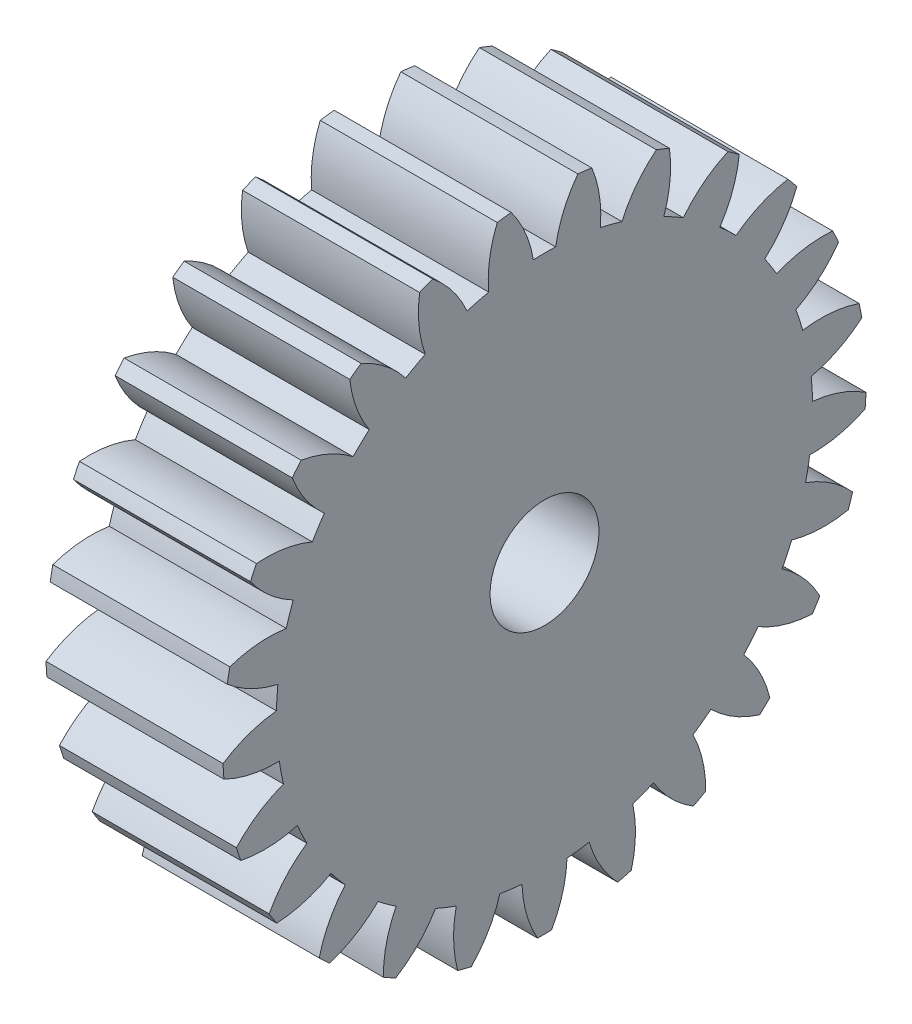
SolidWorks part; units mm, degrees
ref_plane "Plane1" through (0, 0, 0) normal (0, 0, 1) x (1, 0, 0)
ref_plane "Plane2" through (0, 0, 0) normal (0, 1, 0) x (1, 0, 0)
ref_plane "Plane3" through (0, 0, 0) normal (1, 0, 0) x (0, 0, -1)
sketch "HoldingSke" plane through (0, 0, 0) normal (0, 1, 0) x (1, 0, 0)
  line L0 (0, 0) -> (0.5179, -0.2415)
  line L1 (-15, 0) -> (100, 0) construction
  line L2 (0, 0) -> (-2.1039, 2.3779)
  line L3 (0, 0) -> (-11.863, 4.5341)
  line L4 (0, 0) -> (7.8269, 3.6497)
  line L5 (0, 0) -> (-46.8476, -17.4728)
  line L6 (0, 0) -> (-10.7765, -7.2709)
  line L7 (-2.1039, 2.3779) -> (8.6586, 51.2059)
  line L8 (-76.2, 54.61) -> (-74.8, 54.61)
  line L9 (-71.009, 38.7566) -> (-53.1078, 45.2721)
  line L10 (-76.2, 71.12) -> (104.1128, 71.12)
  line L11 (0, 0) -> (-13, 0)
  line L12 (-76.2, 101.6) -> (-76.147, 101.6)
  line L13 (24.9733, 27.94) -> (52.9518, 28.4284)
  line L14 (24.9733, 27.94) -> (24.9743, 27.94)
  line L15 (24.9733, 27.94) -> (100.4006, 29.5858)
  line L16 (-63.627, -1.75) -> (-12.827, -1.75)
  circle A0 centre (0, 0) radius 4
  circle A1 centre (0, 0) radius 19.6865
  circle A2 centre (0, 0) radius 37.5
  circle A3 centre (0, 0) radius 4
  dimension "MHD" = 39.373
  dimension "Hub_dia" = 75
  dimension "Bore" = 8
  dimension "MBD" = 8
  dimension "Num_teeth" = 25
  dimension "Pitch" = 0.5714
  dimension "Overall_len" = 50
  dimension "Show_teeth" = 25
  dimension "Thickness" = 13
  dimension "OAL" = 50.0001
  dimension "T_dim" = 1.4
  dimension "Ap" = 20
  dimension "H" = 19.05
  dimension "Pitch_radius" = 180.3128
  dimension "Width" = 13
  dimension "Backlash" = 0.053
  dimension "Addendum_fac" = 1
  dimension "Dedendum_fac" = 1.25
  dimension "Clearance_fac" = 0.25
  dimension "Dedendum_add" = 0.001
  dimension "Module" = 1.75
sketch "BasProSke" plane through (0, 0, 0) normal (0, 1, 0) x (1, 0, 0)
  line L0 (-10, 0) -> (60, 0) construction
  line L1 (0, 0) -> (0, 23.625)
  line L2 (0, 0) -> (13, 0)
  line L3 (13, 0) -> (13, 23.625)
  line L4 (13, 23.625) -> (0, 23.625)
  dimension "Thickness" = 13
  dimension "Diameter" = 47.25
revolve "Base-Revolve" add sketch "BasProSke" angle 360 about L0
sketch "TooCutSke" plane through (0, 0, 0) normal (1, 0, 0) x (0, 0, -1)
  line L1 (0, 0) -> (0, 107) construction
  line L2 (0, 0) -> (-1.4663, 21.8258) construction
  line L3 (0, 0) -> (-5.4739, 43.3306) construction
  line L4 (-1.4663, 21.8258) -> (-2.737, 21.6653) construction
  arc A0 (0.819, 19.6695) -> (-0.819, 19.6695) centre (0, 0) ccw
  arc A1 (2.4674, 23.5213) -> (-2.4674, 23.5213) centre (0, 0) ccw
  circle A2 centre (0, 0) radius 21.875 construction
  circle A3 centre (0, 0) radius 20.5558 construction
  arc A4 (-0.819, 19.6695) -> (-2.4674, 23.5213) centre (-9.4536, 18.2529) ccw
  arc A5 (2.4674, 23.5213) -> (0.819, 19.6695) centre (9.4536, 18.2529) ccw
  dimension "Root_dia" = 39.373
  dimension "Overcut_dia" = 47.3008
  dimension "Pitch_dia" = 43.75
  dimension "Base_dia" = 41.1116
  dimension "Flank_rad" = 8.75
  dimension "Half_ang" = 7.2
  dimension "Half_CT" = 1.2808
extrude "ToothCut" cut sketch "TooCutSke" along normal through all
fillet "Breaks" [suppressed] radius 0.035
fillet "RootFillets" [suppressed] radius 0.4385
pattern_circular "TeethCuts" count 25 every 14.4 about axis through (-10, 0, 0) along (1, 0, 0) of "ToothCut", "RootFillets", "Breaks"
sketch "HubNeaOneSke" plane through (0, 0, 0) normal (-1, 0, 0) x (0, 0, 1)
  circle A0 centre (0, 0) radius 19.6865
  dimension "Diameter" = 39.373
extrude "HubNearOne" [suppressed] add sketch "HubNeaOneSke" along normal blind 37.0001
sketch "HubNeaBotSke" plane through (0, 0, 0) normal (-1, 0, 0) x (0, 0, 1)
  circle A0 centre (0, 0) radius 19.6865
  dimension "Diameter" = 39.373
extrude "HubNearBoth" [suppressed] add sketch "HubNeaBotSke" along normal blind 18.5
ref_plane "FarPln" through (13, 0, 0) normal (1, 0, 0) x (0, 0, -1)
sketch "HubFarSke" plane through (13, 0, 0) normal (1, 0, 0) x (0, 0, -1)
  circle A0 centre (0, 0) radius 19.6865
  dimension "Diameter" = 39.373
extrude "HubFar" [suppressed] add sketch "HubFarSke" along normal blind 18.5
sketch "BorSke" plane through (0, 0, 0) normal (1, 0, 0) x (0, 0, -1)
  circle A0 centre (0, 0) radius 4
  dimension "Diameter" = 8
extrude "Bore" cut sketch "BorSke" along normal mid plane 100.0001
sketch "KeySke" plane through (0, 0, 0) normal (1, 0, 0) x (0, 0, -1)
  line L0 (-1.5, 0) -> (-1.5, 5.4)
  line L1 (-1.5, 5.4) -> (1.5, 5.4)
  line L2 (1.5, 5.4) -> (1.5, 0)
  line L3 (0, 0) -> (0, 34) construction
  line L4 (-1.5, 0) -> (1.5, 0)
  dimension "Offset" = 5.4
  dimension "Width" = 3
extrude "Keyway" [suppressed] cut sketch "KeySke" along normal mid plane 100.0001
pattern_circular "Keyway2" [suppressed] count 2 every 90 about axis through (-10, 0, 0) along (1, 0, 0)
equation "' \"Module@HoldingSke\" = 6.35"
equation "' \"Num_teeth@HoldingSke\" = 12"
equation "' \"Ap@HoldingSke\" =  20"
equation "' \"Ap@HoldingSke\" = 20"
equation "' \"Width@HoldingSke\" = 0.5 * 25.4"
equation "' \"Hub_dia@HoldingSke\"= 1 * 25.4"
equation "' \"Hub_dia@HoldingSke\" = 1 * 25.4"
equation "' \"Overall_len@HoldingSke\" = 1.0 * 25.4"
equation "' \"Bore@HoldingSke\" = 0.75 * 25.4"
equation "' \"T_dim@HoldingSke\" = 0.1 * 25.4"
equation "' \"Width@KeySke\" = 0.25 * 25.4"
equation "' \"Show_teeth@HoldingSke\" = 13"
equation "' \"Backlash@HoldingSke\" = 0.009 * 25.4"
equation "' \"Addendum_fac@HoldingSke\" = 1.0"
equation "' \"Dedendum_fac@HoldingSke\" = 1.25"
equation "' \"Dedendum_add@HoldingSke\" = 0.00005 * 25.4"
equation "' \"Clearance_fac@HoldingSke\" = 0.25"
equation "\"Pitch@HoldingSke\" = 1 / \"Module@HoldingSke\""
equation "\"Overcut_dia@TooCutSke\" = (\"Num_teeth@HoldingSke\" + 2 * \"Addendum_fac@HoldingSke\") / \"Pitch@HoldingSke\" + 0.002 * 25.4"
equation "\"Pitch_dia@TooCutSke\" = \"Num_teeth@HoldingSke\" / \"Pitch@HoldingSke\""
equation "\"Base_dia@TooCutSke\" = \"Num_teeth@HoldingSke\" / \"Pitch@HoldingSke\" * cos((\"Ap@HoldingSke\"  * 3.14159265 / 180))"
equation "\"Root_dia@TooCutSke\" = (\"Num_teeth@HoldingSke\" + 2) / \"Pitch@HoldingSke\" - 2 * (\"Addendum_fac@HoldingSke\" + \"Dedendum_fac@HoldingSke\") / \"Pitch@HoldingSke\" - \"Dedendum_add@HoldingSke\" * 2"
equation "\"Half_ang@TooCutSke\" = 180 / \"Num_teeth@HoldingSke\""
equation "\"Half_CT@TooCutSke\" = \"Num_teeth@HoldingSke\" / \"Pitch@HoldingSke\" * sin((3.14159265 / 2 / \"Num_teeth@HoldingSke\")) / 2 - 7 * \"Backlash@HoldingSke\" / 4"
equation "\"Flank_rad@TooCutSke\" = \"Num_teeth@HoldingSke\" / \"Pitch@HoldingSke\" / 5"
equation "\"Radius@RootFillets\" = \"Clearance_fac@HoldingSke\" / \"Pitch@HoldingSke\" + \"Dedendum_add@HoldingSke\""
equation "\"Break_rad@Breaks\" = 0.02 / \"Pitch@HoldingSke\""
equation "\"Thickness@HoldingSke\" = \"Width@HoldingSke\""
equation "\"OAL@HoldingSke\" = \"Thickness@HoldingSke\""
equation "\"MHD@HoldingSke\" = (\"Num_teeth@HoldingSke\" + 2) / \"Pitch@HoldingSke\" - 2 * (\"Addendum_fac@HoldingSke\" + \"Dedendum_fac@HoldingSke\")  / \"Pitch@HoldingSke\" - \"Dedendum_add@HoldingSke\" * 2"
equation "\"MBD@HoldingSke\" = (\"Num_teeth@HoldingSke\" + 2) / \"Pitch@HoldingSke\" - 2 * (\"Addendum_fac@HoldingSke\" + \"Dedendum_fac@HoldingSke\")  / \"Pitch@HoldingSke\" - \"Dedendum_add@HoldingSke\" * 2 - 0.002 * 25.4"
equation "\"MHD@HoldingSke\" = ((sgn( \"MHD@HoldingSke\" - \"Hub_dia@HoldingSke\" )-1)*( \"MHD@HoldingSke\" - \"Hub_dia@HoldingSke\" ))/-2+ \"Hub_dia@HoldingSke\""
equation "\"MBD@HoldingSke\" = ((sgn( \"MBD@HoldingSke\" - \"Bore@HoldingSke\" )-1)*( \"MBD@HoldingSke\" - \"Bore@HoldingSke\" ))/-2+ \"Bore@HoldingSke\""
equation "\"OAL@HoldingSke\" = ((sgn( \"OAL@HoldingSke\" - \"Overall_len@HoldingSke\" )+1)*( \"OAL@HoldingSke\" - \"Overall_len@HoldingSke\" ))/2 + \"Overall_len@HoldingSke\" + 0.000002 * 25.4"
equation "\"Num_teeth@TeethCuts\" = int( \"Show_teeth@HoldingSke\" ) + 1"
equation "\"Num_teeth@TeethCuts\" = ((sgn( \"Num_teeth@TeethCuts\" - \"Num_teeth@HoldingSke\" )-1)*( \"Num_teeth@TeethCuts\" - \"Num_teeth@HoldingSke\" ))/-2+ \"Num_teeth@HoldingSke\""
equation "\"Num_teeth@TeethCuts\" = ((sgn( \"Num_teeth@TeethCuts\" - 2.0)+1)*( \"Num_teeth@TeethCuts\" - 2.0))/2 +2.0"
equation "\"Angle@TeethCuts\" = 360.0 / \"Num_teeth@HoldingSke\""
equation "\"Diameter@BasProSke\" = (\"Num_teeth@HoldingSke\" + 2 * \"Addendum_fac@HoldingSke\") / \"Pitch@HoldingSke\""
equation "\"Thickness@BasProSke\"  = \"Thickness@HoldingSke\""
equation "' \"Fillet_rad@BasProSke\" =  \"Thickness@HoldingSke\" * 0.05"
equation "' \"Fillet_rad@BasProSke\" = \"Thickness@HoldingSke\" * 0.05"
equation "\"MHD@HoldingSke\" = ((sgn( \"MHD@HoldingSke\" - \"Root_dia@TooCutSke\" )-1)*( \"MHD@HoldingSke\" - \"Root_dia@TooCutSke\" ))/-2+ \"Root_dia@TooCutSke\""
equation "\"Diameter@HubNeaOneSke\" = \"MHD@HoldingSke\""
equation "\"Length@HubNearOne\" = \"OAL@HoldingSke\" - \"Thickness@BasProSke\""
equation "\"Diameter@HubNeaBotSke\" = \"MHD@HoldingSke\""
equation "\"Length@HubNearBoth\" = ( \"OAL@HoldingSke\" - \"Thickness@BasProSke\" ) / 2.0"
equation "\"Thickness@FarPln\" = \"Thickness@BasProSke\""
equation "\"Diameter@HubFarSke\" = \"MHD@HoldingSke\""
equation "\"Length@HubFar\" = ( \"OAL@HoldingSke\" - \"Thickness@BasProSke\" ) / 2.0"
equation "\"Diameter@BorSke\" = \"MBD@HoldingSke\""
equation "\"D1@Bore\" = \"OAL@HoldingSke\" * 2.0"
equation "\"D1@Keyway\" = \"OAL@HoldingSke\" * 2.0"
equation "\"Offset@KeySke\" = \"T_dim@HoldingSke\" + \"MBD@HoldingSke\" / 2.0"
